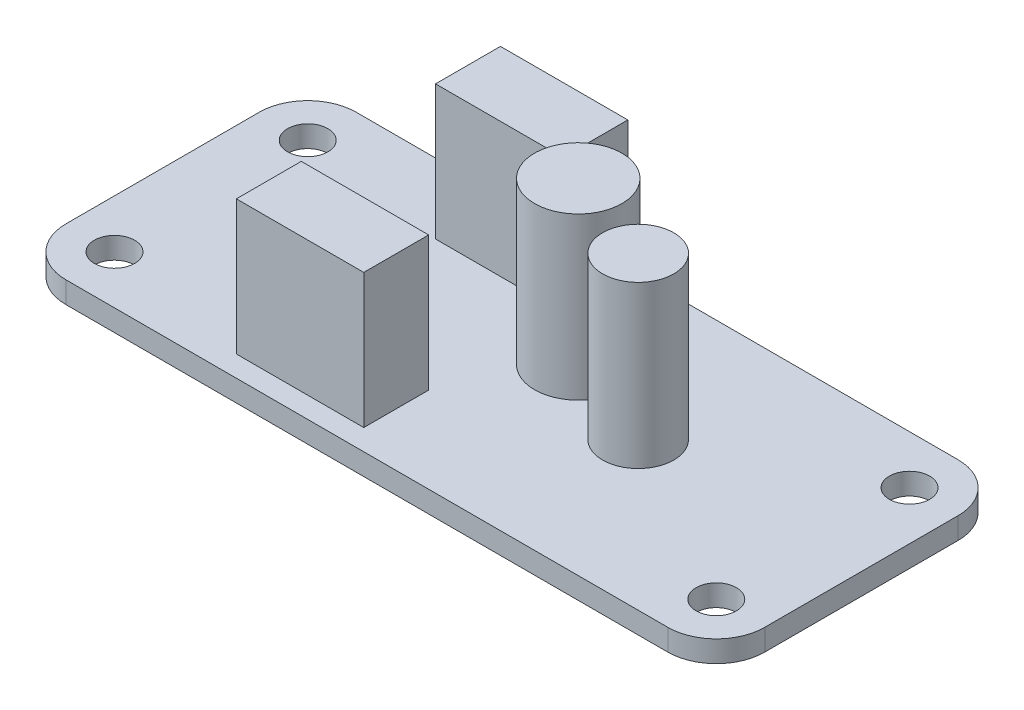
SolidWorks part; units mm, degrees
ref_plane "Front Plane" through (0, 0, 0) normal (0, 0, 1) x (1, 0, 0)
ref_plane "Top Plane" through (0, 0, 0) normal (0, 1, 0) x (1, 0, 0)
ref_plane "Right Plane" through (0, 0, 0) normal (1, 0, 0) x (0, 0, -1)
sketch "Sketch1" plane through (0, 0, 0) normal (0, 1, 0) x (1, 0, 0)
  line L0 (3.61, 0) -> (48.39, 0)
  line L1 (52, 3.61) -> (52, 17.99)
  line L2 (48.39, 21.6) -> (3.61, 21.6)
  line L3 (0, 17.99) -> (0, 3.61)
  circle A0 centre (3.61, 17.99) radius 1.5
  circle A1 centre (48.39, 17.99) radius 1.5
  circle A2 centre (48.39, 3.61) radius 1.5
  circle A3 centre (3.61, 3.61) radius 1.5
  arc A4 (52, 17.99) -> (48.39, 21.6) centre (48.39, 17.99) ccw
  arc A5 (48.39, 0) -> (52, 3.61) centre (48.39, 3.61) ccw
  arc A6 (3.61, 0) -> (0, 3.61) centre (3.61, 3.61) cw
  arc A7 (3.61, 21.6) -> (0, 17.99) centre (3.61, 17.99) ccw
  point P20 (0, 0)
  dimension "D1" = 3.61
  dimension "D9" = 3.61
  dimension "D12" = 3
  dimension "D13" = 3
  dimension "D14" = 3
  dimension "D15" = 3
  dimension "D2" = 3.61
  dimension "D3" = 3.61
  dimension "D4" = 3.61
  dimension "D5" = 3.61
  dimension "D6" = 3.61
  dimension "D7" = 3.61
  dimension "D8" = 3.61
  dimension "D10" = 52
  dimension "D11" = 21.6
extrude "Boss-Extrude1" add sketch "Sketch1" along normal blind 1.6
sketch "Sketch2" plane through (0, 1.6, 0) normal (0, 1, 0) x (1, 0, 0)
  line L0 (3.61, 0) -> (48.39, 0) construction
  line L1 (14.73, 21.21) -> (24.21, 21.21)
  line L2 (14.73, 21.21) -> (14.73, 16.38)
  line L3 (14.73, 16.38) -> (24.21, 16.38)
  line L4 (24.21, 21.21) -> (24.21, 16.38)
  line L5 (14.73, 6.39) -> (24.21, 6.39)
  line L6 (14.73, 6.39) -> (14.73, 1.56)
  line L7 (14.73, 1.56) -> (24.21, 1.56)
  line L8 (24.21, 6.39) -> (24.21, 1.56)
  line L9 (48.39, 21.6) -> (3.61, 21.6) construction
  line L10 (0, 17.99) -> (0, 3.61) construction
  dimension "D1" = 4.83
  dimension "D2" = 4.83
  dimension "D3" = 9.48
  dimension "D4" = 9.48
  dimension "D5" = 1.56
  dimension "D6" = 0.39
  dimension "D7" = 14.73
  dimension "D8" = 14.73
extrude "Boss-Extrude2" add sketch "Sketch2" along normal blind 10 contours L8 L5 L6 L7 | L4 L1 L2 L3
sketch "Sketch3" plane through (0, 1.6, 0) normal (0, 1, 0) x (1, 0, 0)
  line L0 (3.61, 0) -> (48.39, 0) construction
  line L1 (52, 3.61) -> (52, 17.99) construction
  line L2 (48.39, 21.6) -> (3.61, 21.6) construction
  circle A0 centre (35.19, 11) radius 2.65
  circle A1 centre (28.13, 13.6) radius 3.25
  dimension "D1" = 6.5
  dimension "D2" = 5.3
  dimension "D3" = 11
  dimension "D4" = 16.81
  dimension "D5" = 23.87
  dimension "D6" = 8
extrude "Boss-Extrude3" add sketch "Sketch3" along normal blind 12
